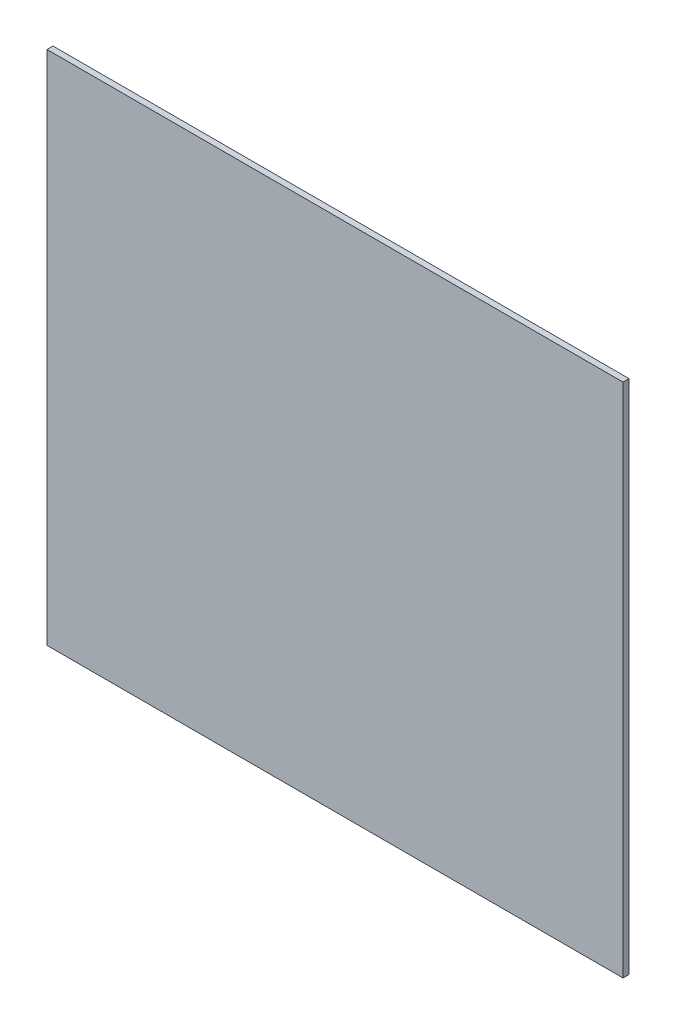
SolidWorks part; units mm, degrees
material "Al homeycomb"
ref_plane "Front Plane" through (0, 0, 0) normal (0, 0, 1) x (1, 0, 0)
ref_plane "Top Plane" through (0, 0, 0) normal (0, 1, 0) x (1, 0, 0)
ref_plane "Right Plane" through (0, 0, 0) normal (1, 0, 0) x (0, 0, -1)
sketch "Sketch1" plane through (0, 0, 0) normal (0, 0, 1) x (1, 0, 0)
  line L1 (-1200, -1075) -> (1200, -1075)
  line L2 (-1200, -1075) -> (-1200, 1075)
  line L3 (-1200, 1075) -> (1200, 1075)
  line L4 (1200, -1075) -> (1200, 1075)
  line L5 (-1200, -1075) -> (1200, 1075) construction
  line L6 (-1200, 1075) -> (1200, -1075) construction
  point P0 (0, 0)
  dimension "D1" = 2400
  dimension "D2" = 2150
extrude "Boss-Extrude1" add sketch "Sketch1" along normal blind 25
